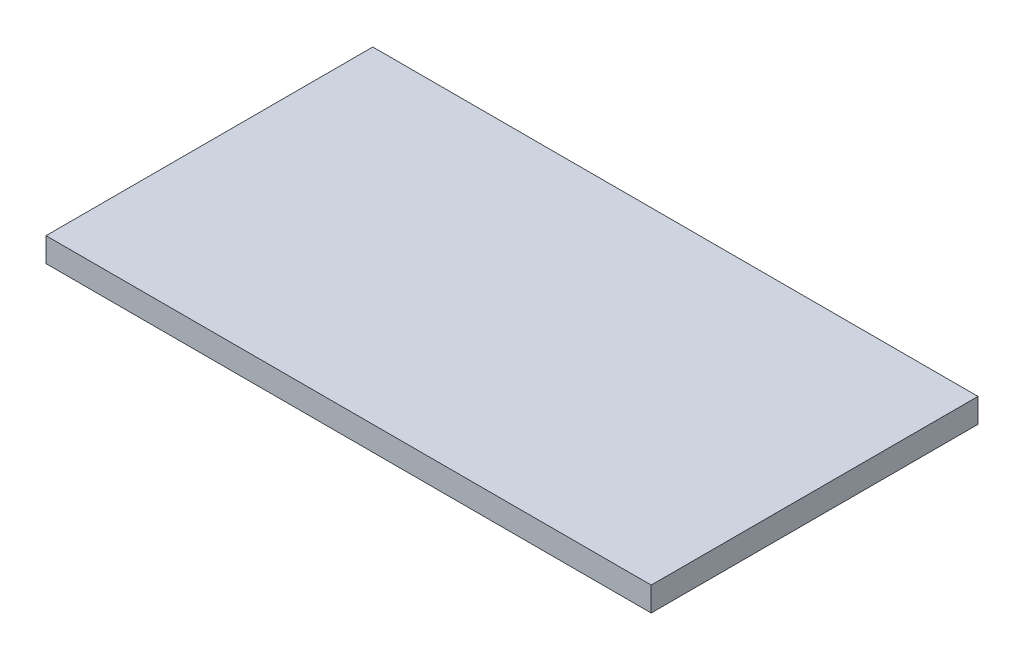
SolidWorks part; units mm, degrees
ref_plane "Front Plane" through (0, 0, 0) normal (0, 0, 1) x (1, 0, 0)
ref_plane "Top Plane" through (0, 0, 0) normal (0, 1, 0) x (1, 0, 0)
ref_plane "Right Plane" through (0, 0, 0) normal (1, 0, 0) x (0, 0, -1)
sketch "Sketch1" plane through (0, 0, 0) normal (0, 1, 0) x (1, 0, 0)
  line L1 (25, -13.5) -> (-25, -13.5)
  line L2 (25, -13.5) -> (25, 13.5)
  line L3 (25, 13.5) -> (-25, 13.5)
  line L4 (-25, -13.5) -> (-25, 13.5)
  line L5 (25, -13.5) -> (-25, 13.5) construction
  line L6 (25, 13.5) -> (-25, -13.5) construction
  point P0 (0, 0)
  dimension "D1" = 50
  dimension "D2" = 27
extrude "Boss-Extrude1" add sketch "Sketch1" along normal blind 2
